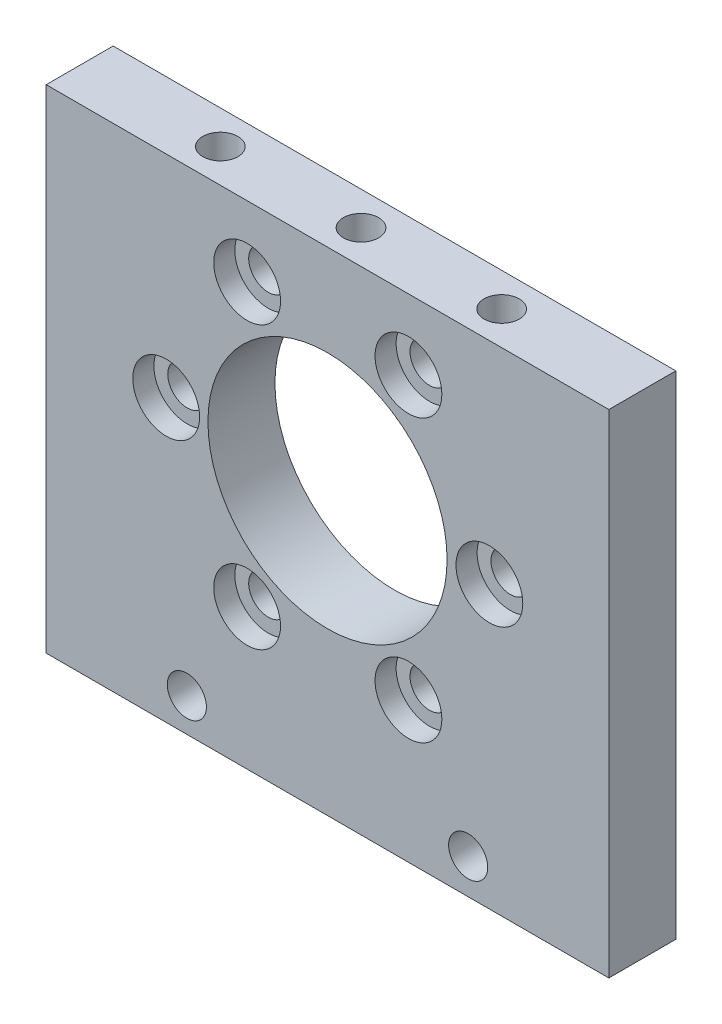
SolidWorks part; units mm, degrees
ref_plane "Plano frontal" through (0, 0, 0) normal (0, 0, 1) x (1, 0, 0)
ref_plane "Plano superior" through (0, 0, 0) normal (0, 1, 0) x (1, 0, 0)
ref_plane "Plano direito" through (0, 0, 0) normal (1, 0, 0) x (0, 0, -1)
sketch "Esboço2" plane through (0, 0, 0) normal (0, 0, 1) x (1, 0, 0)
  line L0 (-40, 0) -> (40, 0) construction
  line L1 (-40, 35) -> (-40, 0)
  line L2 (40, 35) -> (40, 0)
  line L4 (40, 35) -> (-40, 35)
  line L23 (-40, 0) -> (-40, -35)
  line L24 (-40, -35) -> (40, -35)
  line L25 (40, -35) -> (40, 0)
  dimension "D1" = 35
  dimension "D2" = 35
extrude "Ressalto-extrusão1" add sketch "Esboço2" along normal blind 9.525
sketch "Esboço3" plane through (0, 35, 0) normal (0, 1, 0) x (-1, 0, 0)
  line L0 (40, 4.7625) -> (-40, 4.7625) construction
  line L1 (40, 9.525) -> (40, 0) construction
  line L2 (-40, 9.525) -> (-40, 0) construction
  circle A0 centre (20, 4.7625) radius 2.5
  circle A1 centre (0, 4.7625) radius 2.5
  circle A2 centre (-20, 4.7625) radius 2.5
  dimension "D1" = 5
  dimension "D4" = 5
  dimension "D5" = 5
  dimension "D2" = 20
  dimension "D3" = 20
extrude "Corte-extrusão1" cut sketch "Esboço3" against normal blind 23
sketch "Esboço11" plane through (0, 0, 9.525) normal (0, 0, 1) x (1, 0, 0)
  line L0 (-40, -30.2375) -> (40, -30.2375) construction
  circle A0 centre (-20, -30.2375) radius 2.78
  circle A1 centre (20, -30) radius 2.78
  dimension "D3" = 5.56
  dimension "D4" = 5.56
  dimension "D1" = 4.7625
  dimension "D2" = 20
extrude "Corte-extrusão4" cut sketch "Esboço11" against normal up to surface (9.525 mm away) up to face at (0, 0, 0)
sketch "Esboço13" plane through (0, 0, 0) normal (0, 0, -1) x (-1, 0, 0)
  line L0 (-40, 35) -> (40, 35) construction
  circle A0 centre (0, 5) radius 17
  dimension "D1" = 34
  dimension "D2" = 30
extrude "Corte-extrusão5" cut sketch "Esboço13" against normal blind 10
sketch "Esboço14" plane through (0, 0, 0) normal (0, 0, -1) x (-1, 0, 0)
  line L0 (-11.5075, 25) -> (-23.015, 5) construction
  line L1 (-23.015, 5) -> (-11.5075, -15) construction
  line L2 (-11.5075, -15) -> (11.4286, -15) construction
  line L3 (11.4286, -15) -> (22.9361, 5) construction
  line L4 (22.9361, 5) -> (11.4286, 25) construction
  line L5 (11.4286, 25) -> (-11.5075, 25) construction
  circle A0 centre (-23.015, 5) radius 2.78
  circle A1 centre (-11.5075, -15) radius 2.78
  circle A2 centre (-11.5075, 25) radius 2.78
  circle A3 centre (11.4286, 25) radius 2.78
  circle A4 centre (22.9361, 5) radius 2.78
  circle A5 centre (11.4286, -15) radius 2.78
  dimension "D1" = 5.56
  dimension "D2" = 5.56
  dimension "D3" = 5.56
  dimension "D4" = 5.56
  dimension "D5" = 5.56
  dimension "D6" = 5.56
  dimension "D7" = 20
  dimension "D8" = 20
  dimension "D9" = 30
  dimension "D10" = 20
  dimension "D11" = 28.5714
  dimension "D12" = 28.4925
  dimension "D13" = 28.4925
  dimension "D14" = 22.9361
  dimension "D15" = 22.9361
extrude "Corte-extrusão6" cut sketch "Esboço14" against normal blind 9.525 contours A4 | A3 | A2 | A0 | A1 | A5
sketch "Esboço16" plane through (0, 0, 9.525) normal (0, 0, 1) x (1, 0, 0)
  circle A0 centre (-22.9361, 5) radius 4.75
  circle A1 centre (-11.4286, 25) radius 4.75
  circle A2 centre (11.5075, 25) radius 4.75
  circle A3 centre (23.015, 5) radius 4.75
  circle A4 centre (11.5075, -15) radius 4.75
  circle A5 centre (-11.4286, -15) radius 4.75
  dimension "D1" = 9.5
  dimension "D2" = 9.5
  dimension "D3" = 9.5
  dimension "D4" = 9.5
  dimension "D5" = 9.5
  dimension "D6" = 9.5
extrude "Corte-extrusão9" cut sketch "Esboço16" against normal blind 3
